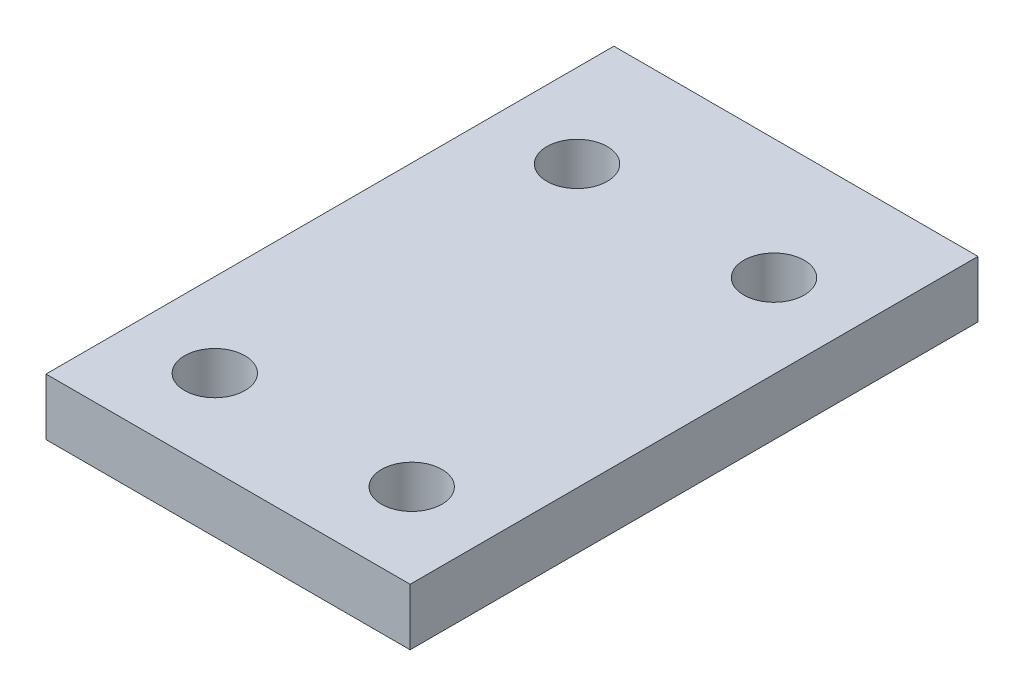
SolidWorks part; units mm, degrees
ref_plane "Front Plane" through (0, 0, 0) normal (0, 0, 1) x (1, 0, 0)
ref_plane "Top Plane" through (0, 0, 0) normal (0, 1, 0) x (1, 0, 0)
ref_plane "Right Plane" through (0, 0, 0) normal (1, 0, 0) x (0, 0, -1)
sketch "Sketch1" plane through (0, 0, 0) normal (0, 1, 0) x (1, 0, 0)
  line L0 (0, -1000) -> (0, 49000) construction
  line L1 (-20.3581, -31.75) -> (20.3581, -31.75)
  line L2 (-20.3581, -31.75) -> (-20.3581, 31.75)
  line L3 (-20.3581, 31.75) -> (20.3581, 31.75)
  line L4 (20.3581, -31.75) -> (20.3581, 31.75)
  line L5 (-20.3581, -31.75) -> (20.3581, 31.75) construction
  line L6 (-20.3581, 31.75) -> (20.3581, -31.75) construction
  circle A0 centre (11.0109, 18.288) radius 3.3782
  circle A1 centre (11.0109, -22.225) radius 3.3782
  circle A2 centre (-11.0109, -22.225) radius 3.3782
  circle A3 centre (-11.0109, 18.288) radius 3.3782
  point P0 (0, 0)
  dimension "D6" = 6.7564
  dimension "D1" = 40.7162
  dimension "D2" = 63.5
  dimension "D3" = 13.462
  dimension "D4" = 9.525
  dimension "D5" = 9.3472
extrude "Boss-Extrude1" add sketch "Sketch1" along normal blind 6.35
